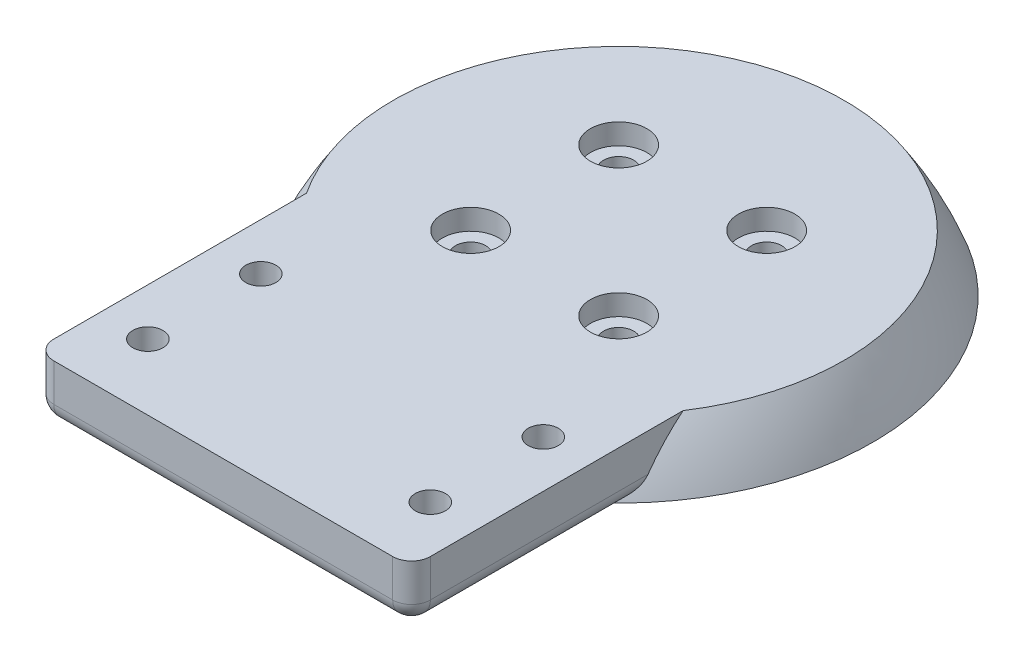
SolidWorks part; units mm, degrees
material "自定义塑料"
ref_plane "前视基准面" through (0, 0, 0) normal (0, 0, 1) x (1, 0, 0)
ref_plane "上视基准面" through (0, 0, 0) normal (0, 1, 0) x (1, 0, 0)
ref_plane "右视基准面" through (0, 0, 0) normal (1, 0, 0) x (0, 0, -1)
sketch "草图14" plane through (0, 0, 0) normal (0, 0, 1) x (1, 0, 0)
  line L1 (0, 18.7924) -> (0, 0)
  line L3 (0, 0) -> (27, 0)
  arc A0 (27, 0) -> (0, 18.7924) centre (0, -10) ccw
  point P4 (0, 0)
revolve "旋转4" add sketch "草图14" angle 360 about L1
sketch "草图15" plane through (0, 0, 0) normal (0, 0, 1) x (1, 0, 0)
  line L0 (0, 18.7924) -> (0, 0)
  line L2 (-20, 18.7924) -> (20, 18.7924)
  line L3 (-20, 18.7924) -> (-20, 0)
  line L4 (-20, 0) -> (20, 0)
  line L5 (20, 18.7924) -> (20, 0)
  line L6 (-20, 18.7924) -> (20, 0) construction
  line L7 (-20, 0) -> (20, 18.7924) construction
  arc A0 (27, 0) -> (-27, 0) centre (0, -10) ccw construction
  point P5 (0, 9.3962)
  dimension "D1" = 40
extrude "凸台-拉伸5" add sketch "草图15" along normal blind 42 contours L2 L5 L4 L3
sketch "草图16" plane through (0, 0, 42) normal (0, 0, 1) x (1, 0, 0)
  line L0 (0, 0) -> (0, 6)
  line L1 (0, 6) -> (23.9374, 6)
  line L2 (23.9374, 6) -> (23.9374, 21.459)
  line L3 (23.9374, 21.459) -> (-28.8979, 21.459)
  line L4 (-28.8979, 21.459) -> (-28.8979, 6)
  line L6 (-28.8979, 6) -> (0, 6)
  arc A0 (27, 0) -> (20, 10.7123) centre (0, -10) ccw construction
  line M1 (-20, 18.7924) -> (-20, 0)
  line M3 (20, 0) -> (20, 18.7924)
  line M4 (20, 18.7924) -> (-20, 18.7924)
  dimension "D1" = 6
extrude "切除-拉伸9" cut sketch "草图16" against normal through all contours L6 L1 M1 M3 M4 | L4 L6 L1 L2 L3 M1 M4 M3
sketch "草图17" plane through (0, 6, 0) normal (0, 1, 0) x (1, 0, 0)
  line L1 (-7.86, 7.86) -> (7.86, 7.86)
  line L2 (-7.86, 7.86) -> (-7.86, -7.86)
  line L3 (-7.86, -7.86) -> (7.86, -7.86)
  line L4 (7.86, 7.86) -> (7.86, -7.86)
  line L5 (-7.86, 7.86) -> (7.86, -7.86) construction
  line L6 (-7.86, -7.86) -> (7.86, 7.86) construction
  circle A0 centre (7.86, 7.86) radius 1.6
  circle A1 centre (7.86, -7.86) radius 1.6
  circle A2 centre (-7.86, -7.86) radius 1.6
  circle A3 centre (-7.86, 7.86) radius 1.6
  point P0 (0, 0)
  point P16 (0, 0)
  dimension "D1" = 4
extrude "切除-拉伸10" cut sketch "草图17" against normal through all contours L1 A3 L2 | L2 A3 L1 | L1 A0 L4 | L4 A0 L1 | L3 A1 L4 | L4 A1 L3 | L3 A2 L2 | L2 A2 L3
sketch "草图18" plane through (0, 6, 0) normal (0, 1, 0) x (1, 0, 0)
  line L1 (-7.86, 7.86) -> (7.86, 7.86)
  line L2 (-7.86, 7.86) -> (-7.86, -7.86)
  line L3 (-7.86, -7.86) -> (7.86, -7.86)
  line L4 (7.86, 7.86) -> (7.86, -7.86)
  line L5 (-7.86, 7.86) -> (7.86, -7.86) construction
  line L6 (-7.86, -7.86) -> (7.86, 7.86) construction
  circle A0 centre (7.86, 7.86) radius 3
  circle A1 centre (7.86, -7.86) radius 3
  circle A2 centre (-7.86, -7.86) radius 3
  circle A3 centre (-7.86, 7.86) radius 3
  point P0 (0, 0)
  point P16 (0, 0)
  dimension "D1" = 6
  dimension "D2" = 4
extrude "切除-拉伸11" cut sketch "草图18" against normal blind 2.2 contours A3 | A0 | A1 | A2
sketch "草图19" plane through (0, 6, 0) normal (0, 1, 0) x (1, 0, 0)
  line L0 (0, 0) -> (0, -29.0025)
  line L7 (15, -23.0025) -> (-15, -23.0025)
  line L8 (15, -23.0025) -> (15, -35.0025)
  line L9 (15, -35.0025) -> (-15, -35.0025)
  line L10 (-15, -23.0025) -> (-15, -35.0025)
  line L11 (15, -23.0025) -> (-15, -35.0025) construction
  line L12 (15, -35.0025) -> (-15, -23.0025) construction
  circle A0 centre (0, 0) radius 27
  circle A5 centre (15, -23.0025) radius 1.6
  circle A6 centre (-15, -23.0025) radius 1.6
  circle A7 centre (-15, -35.0025) radius 1.6
  circle A8 centre (15, -35.0025) radius 1.6
extrude "切除-拉伸12" cut sketch "草图19" against normal through all
sketch "草图20" plane through (0, 0, 0) normal (0, -1, 0) x (1, 0, 0)
  line L25 (-15, 31.7116) -> (-12.15, 33.3571)
  line L26 (15, 31.7116) -> (17.85, 33.3571)
  line L27 (17.85, 33.3571) -> (17.85, 36.648)
  line L28 (17.85, 36.648) -> (15, 38.2934)
  line L29 (15, 38.2934) -> (12.15, 36.648)
  line L30 (12.15, 36.648) -> (12.15, 33.3571)
  line L31 (12.15, 33.3571) -> (15, 31.7116)
  line L32 (-12.15, 33.3571) -> (-12.15, 36.648)
  line L33 (-12.15, 36.648) -> (-15, 38.2934)
  line L34 (-15, 38.2934) -> (-17.85, 36.648)
  line L35 (-17.85, 36.648) -> (-17.85, 33.3571)
  line L36 (-17.85, 33.3571) -> (-15, 31.7116)
  line L37 (-15, 19.7116) -> (-12.15, 21.3571)
  line L38 (-12.15, 21.3571) -> (-12.15, 24.648)
  line L39 (-12.15, 24.648) -> (-15, 26.2934)
  line L40 (-15, 26.2934) -> (-17.85, 24.648)
  line L41 (-17.85, 24.648) -> (-17.85, 21.3571)
  line L42 (-17.85, 21.3571) -> (-15, 19.7116)
  line L43 (15, 19.7116) -> (17.85, 21.3571)
  line L44 (17.85, 21.3571) -> (17.85, 24.648)
  line L45 (17.85, 24.648) -> (15, 26.2934)
  line L46 (15, 26.2934) -> (12.15, 24.648)
  line L47 (12.15, 24.648) -> (12.15, 21.3571)
  line L48 (12.15, 21.3571) -> (15, 19.7116)
  circle A0 centre (15, 35.0025) radius 2.85 construction
  circle A1 centre (-15, 35.0025) radius 2.85 construction
  circle A2 centre (-15, 23.0025) radius 2.85 construction
  circle A3 centre (15, 23.0025) radius 2.85 construction
  dimension "D1" = 5.7
extrude "切除-拉伸13" cut sketch "草图20" against normal blind 2.2
fillet "圆角2" radius 2 5 edges at (20, 0, 30.0692) (20, 3, 42) (0, 0, 42) (-20, 3, 42) (-20, 0, 30.0692)
